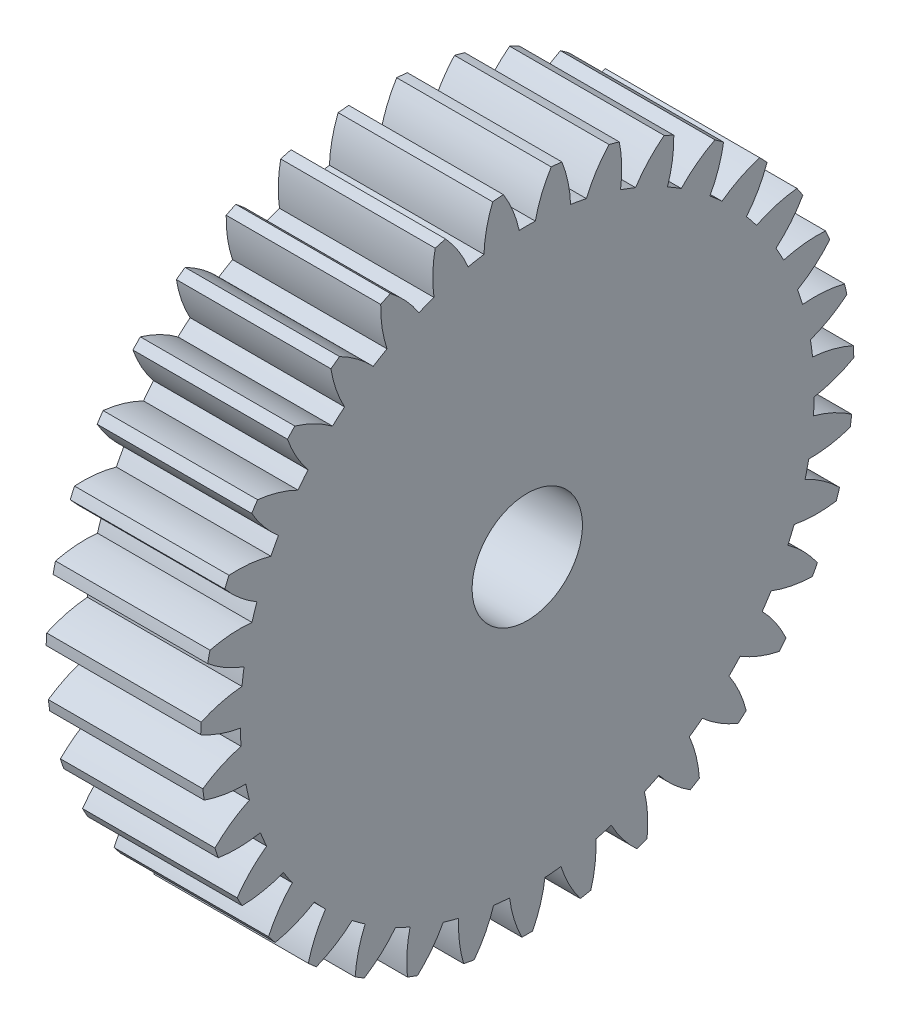
SolidWorks part; units mm, degrees
ref_plane "Plane1" through (0, 0, 0) normal (0, 0, 1) x (1, 0, 0)
ref_plane "Plane2" through (0, 0, 0) normal (0, 1, 0) x (1, 0, 0)
ref_plane "Plane3" through (0, 0, 0) normal (1, 0, 0) x (0, 0, -1)
sketch "HoldingSke" plane through (0, 0, 0) normal (0, 1, 0) x (1, 0, 0)
  line L0 (0, 0) -> (1.0239, -0.717)
  line L1 (-15, 0) -> (100, 0) construction
  line L2 (0, 0) -> (-2.1039, 2.3779)
  line L3 (0, 0) -> (-11.863, 4.5341)
  line L4 (0, 0) -> (7.0742, 4.9534)
  line L5 (0, 0) -> (-46.8476, -17.4728)
  line L6 (0, 0) -> (-5.8027, -3.9151)
  line L7 (-2.1039, 2.3779) -> (8.6586, 51.2059)
  line L8 (-76.2, 54.61) -> (-75.3, 54.61)
  line L9 (-71.009, 38.7566) -> (-53.1078, 45.2721)
  line L10 (-76.2, 71.12) -> (104.1128, 71.12)
  line L11 (0, 0) -> (-7, 0)
  line L12 (-76.2, 101.6) -> (-76.17, 101.6)
  line L13 (24.9733, 27.94) -> (52.9518, 28.4284)
  line L14 (24.9733, 27.94) -> (24.9743, 27.94)
  line L15 (24.9733, 27.94) -> (100.4006, 29.5858)
  line L16 (-63.627, -0.8) -> (-12.827, -0.8)
  circle A0 centre (0, 0) radius 2.5
  circle A1 centre (0, 0) radius 12.999
  circle A2 centre (0, 0) radius 37.5
  circle A3 centre (0, 0) radius 2.5
  dimension "MHD" = 25.998
  dimension "Hub_dia" = 75
  dimension "Bore" = 5
  dimension "MBD" = 5
  dimension "Num_teeth" = 35
  dimension "Pitch" = 1.25
  dimension "Overall_len" = 50
  dimension "Show_teeth" = 35
  dimension "Thickness" = 7
  dimension "OAL" = 50.0001
  dimension "T_dim" = 0.9
  dimension "Ap" = 20
  dimension "H" = 19.05
  dimension "Pitch_radius" = 180.3128
  dimension "Width" = 7
  dimension "Backlash" = 0.03
  dimension "Addendum_fac" = 1
  dimension "Dedendum_fac" = 1.25
  dimension "Clearance_fac" = 0.25
  dimension "Dedendum_add" = 0.001
  dimension "Module" = 0.8
sketch "BasProSke" plane through (0, 0, 0) normal (0, 1, 0) x (1, 0, 0)
  line L0 (-10, 0) -> (60, 0) construction
  line L1 (0, 0) -> (0, 14.8)
  line L2 (0, 0) -> (7, 0)
  line L3 (7, 0) -> (7, 14.8)
  line L4 (7, 14.8) -> (0, 14.8)
  dimension "Thickness" = 7
  dimension "Diameter" = 29.6
revolve "Base-Revolve" add sketch "BasProSke" angle 360 about L0
sketch "TooCutSke" plane through (0, 0, 0) normal (1, 0, 0) x (0, 0, -1)
  line L1 (0, 0) -> (0, 107) construction
  line L2 (0, 0) -> (-0.6806, 13.9834) construction
  line L3 (0, 0) -> (-2.5078, 27.8637) construction
  line L4 (-0.6806, 13.9834) -> (-1.2539, 13.9318) construction
  arc A0 (0.3644, 12.9939) -> (-0.3644, 12.9939) centre (0, 0) ccw
  arc A1 (1.1007, 14.7845) -> (-1.1007, 14.7845) centre (0, 0) ccw
  circle A2 centre (0, 0) radius 14 construction
  circle A3 centre (0, 0) radius 13.1557 construction
  arc A4 (-0.3644, 12.9939) -> (-1.1007, 14.7845) centre (-5.8338, 11.7915) ccw
  arc A5 (1.1007, 14.7845) -> (0.3644, 12.9939) centre (5.8338, 11.7915) ccw
  dimension "Root_dia" = 25.998
  dimension "Overcut_dia" = 29.6508
  dimension "Pitch_dia" = 28
  dimension "Base_dia" = 26.3114
  dimension "Flank_rad" = 5.6
  dimension "Half_ang" = 5.143
  dimension "Half_CT" = 0.5756
extrude "ToothCut" cut sketch "TooCutSke" along normal through all
fillet "Breaks" [suppressed] radius 0.016
fillet "RootFillets" [suppressed] radius 0.201
pattern_circular "TeethCuts" count 35 every 10.286 about axis through (-10, 0, 0) along (1, 0, 0) of "ToothCut", "RootFillets", "Breaks"
sketch "HubNeaOneSke" plane through (0, 0, 0) normal (-1, 0, 0) x (0, 0, 1)
  circle A0 centre (0, 0) radius 12.999
  dimension "Diameter" = 25.998
extrude "HubNearOne" [suppressed] add sketch "HubNeaOneSke" along normal blind 43.0001
sketch "HubNeaBotSke" plane through (0, 0, 0) normal (-1, 0, 0) x (0, 0, 1)
  circle A0 centre (0, 0) radius 12.999
  dimension "Diameter" = 25.998
extrude "HubNearBoth" [suppressed] add sketch "HubNeaBotSke" along normal blind 21.5
ref_plane "FarPln" through (7, 0, 0) normal (1, 0, 0) x (0, 0, -1)
sketch "HubFarSke" plane through (7, 0, 0) normal (1, 0, 0) x (0, 0, -1)
  circle A0 centre (0, 0) radius 12.999
  dimension "Diameter" = 25.998
extrude "HubFar" [suppressed] add sketch "HubFarSke" along normal blind 21.5
sketch "BorSke" plane through (0, 0, 0) normal (1, 0, 0) x (0, 0, -1)
  circle A0 centre (0, 0) radius 2.5
  dimension "Diameter" = 5
extrude "Bore" cut sketch "BorSke" along normal mid plane 100.0001
sketch "KeySke" plane through (0, 0, 0) normal (1, 0, 0) x (0, 0, -1)
  line L0 (-1, 0) -> (-1, 3.4)
  line L1 (-1, 3.4) -> (1, 3.4)
  line L2 (1, 3.4) -> (1, 0)
  line L3 (0, 0) -> (0, 34) construction
  line L4 (-1, 0) -> (1, 0)
  dimension "Offset" = 3.4
  dimension "Width" = 2
extrude "Keyway" [suppressed] cut sketch "KeySke" along normal mid plane 100.0001
pattern_circular "Keyway2" [suppressed] count 2 every 90 about axis through (-10, 0, 0) along (1, 0, 0)
equation "' \"Module@HoldingSke\" = 6.35"
equation "' \"Num_teeth@HoldingSke\" = 12"
equation "' \"Ap@HoldingSke\" =  20"
equation "' \"Ap@HoldingSke\" = 20"
equation "' \"Width@HoldingSke\" = 0.5 * 25.4"
equation "' \"Hub_dia@HoldingSke\"= 1 * 25.4"
equation "' \"Hub_dia@HoldingSke\" = 1 * 25.4"
equation "' \"Overall_len@HoldingSke\" = 1.0 * 25.4"
equation "' \"Bore@HoldingSke\" = 0.75 * 25.4"
equation "' \"T_dim@HoldingSke\" = 0.1 * 25.4"
equation "' \"Width@KeySke\" = 0.25 * 25.4"
equation "' \"Show_teeth@HoldingSke\" = 13"
equation "' \"Backlash@HoldingSke\" = 0.009 * 25.4"
equation "' \"Addendum_fac@HoldingSke\" = 1.0"
equation "' \"Dedendum_fac@HoldingSke\" = 1.25"
equation "' \"Dedendum_add@HoldingSke\" = 0.00005 * 25.4"
equation "' \"Clearance_fac@HoldingSke\" = 0.25"
equation "\"Pitch@HoldingSke\" = 1 / \"Module@HoldingSke\""
equation "\"Overcut_dia@TooCutSke\" = (\"Num_teeth@HoldingSke\" + 2 * \"Addendum_fac@HoldingSke\") / \"Pitch@HoldingSke\" + 0.002 * 25.4"
equation "\"Pitch_dia@TooCutSke\" = \"Num_teeth@HoldingSke\" / \"Pitch@HoldingSke\""
equation "\"Base_dia@TooCutSke\" = \"Num_teeth@HoldingSke\" / \"Pitch@HoldingSke\" * cos((\"Ap@HoldingSke\"  * 3.14159265 / 180))"
equation "\"Root_dia@TooCutSke\" = (\"Num_teeth@HoldingSke\" + 2) / \"Pitch@HoldingSke\" - 2 * (\"Addendum_fac@HoldingSke\" + \"Dedendum_fac@HoldingSke\") / \"Pitch@HoldingSke\" - \"Dedendum_add@HoldingSke\" * 2"
equation "\"Half_ang@TooCutSke\" = 180 / \"Num_teeth@HoldingSke\""
equation "\"Half_CT@TooCutSke\" = \"Num_teeth@HoldingSke\" / \"Pitch@HoldingSke\" * sin((3.14159265 / 2 / \"Num_teeth@HoldingSke\")) / 2 - 7 * \"Backlash@HoldingSke\" / 4"
equation "\"Flank_rad@TooCutSke\" = \"Num_teeth@HoldingSke\" / \"Pitch@HoldingSke\" / 5"
equation "\"Radius@RootFillets\" = \"Clearance_fac@HoldingSke\" / \"Pitch@HoldingSke\" + \"Dedendum_add@HoldingSke\""
equation "\"Break_rad@Breaks\" = 0.02 / \"Pitch@HoldingSke\""
equation "\"Thickness@HoldingSke\" = \"Width@HoldingSke\""
equation "\"OAL@HoldingSke\" = \"Thickness@HoldingSke\""
equation "\"MHD@HoldingSke\" = (\"Num_teeth@HoldingSke\" + 2) / \"Pitch@HoldingSke\" - 2 * (\"Addendum_fac@HoldingSke\" + \"Dedendum_fac@HoldingSke\")  / \"Pitch@HoldingSke\" - \"Dedendum_add@HoldingSke\" * 2"
equation "\"MBD@HoldingSke\" = (\"Num_teeth@HoldingSke\" + 2) / \"Pitch@HoldingSke\" - 2 * (\"Addendum_fac@HoldingSke\" + \"Dedendum_fac@HoldingSke\")  / \"Pitch@HoldingSke\" - \"Dedendum_add@HoldingSke\" * 2 - 0.002 * 25.4"
equation "\"MHD@HoldingSke\" = ((sgn( \"MHD@HoldingSke\" - \"Hub_dia@HoldingSke\" )-1)*( \"MHD@HoldingSke\" - \"Hub_dia@HoldingSke\" ))/-2+ \"Hub_dia@HoldingSke\""
equation "\"MBD@HoldingSke\" = ((sgn( \"MBD@HoldingSke\" - \"Bore@HoldingSke\" )-1)*( \"MBD@HoldingSke\" - \"Bore@HoldingSke\" ))/-2+ \"Bore@HoldingSke\""
equation "\"OAL@HoldingSke\" = ((sgn( \"OAL@HoldingSke\" - \"Overall_len@HoldingSke\" )+1)*( \"OAL@HoldingSke\" - \"Overall_len@HoldingSke\" ))/2 + \"Overall_len@HoldingSke\" + 0.000002 * 25.4"
equation "\"Num_teeth@TeethCuts\" = int( \"Show_teeth@HoldingSke\" ) + 1"
equation "\"Num_teeth@TeethCuts\" = ((sgn( \"Num_teeth@TeethCuts\" - \"Num_teeth@HoldingSke\" )-1)*( \"Num_teeth@TeethCuts\" - \"Num_teeth@HoldingSke\" ))/-2+ \"Num_teeth@HoldingSke\""
equation "\"Num_teeth@TeethCuts\" = ((sgn( \"Num_teeth@TeethCuts\" - 2.0)+1)*( \"Num_teeth@TeethCuts\" - 2.0))/2 +2.0"
equation "\"Angle@TeethCuts\" = 360.0 / \"Num_teeth@HoldingSke\""
equation "\"Diameter@BasProSke\" = (\"Num_teeth@HoldingSke\" + 2 * \"Addendum_fac@HoldingSke\") / \"Pitch@HoldingSke\""
equation "\"Thickness@BasProSke\"  = \"Thickness@HoldingSke\""
equation "' \"Fillet_rad@BasProSke\" =  \"Thickness@HoldingSke\" * 0.05"
equation "' \"Fillet_rad@BasProSke\" = \"Thickness@HoldingSke\" * 0.05"
equation "\"MHD@HoldingSke\" = ((sgn( \"MHD@HoldingSke\" - \"Root_dia@TooCutSke\" )-1)*( \"MHD@HoldingSke\" - \"Root_dia@TooCutSke\" ))/-2+ \"Root_dia@TooCutSke\""
equation "\"Diameter@HubNeaOneSke\" = \"MHD@HoldingSke\""
equation "\"Length@HubNearOne\" = \"OAL@HoldingSke\" - \"Thickness@BasProSke\""
equation "\"Diameter@HubNeaBotSke\" = \"MHD@HoldingSke\""
equation "\"Length@HubNearBoth\" = ( \"OAL@HoldingSke\" - \"Thickness@BasProSke\" ) / 2.0"
equation "\"Thickness@FarPln\" = \"Thickness@BasProSke\""
equation "\"Diameter@HubFarSke\" = \"MHD@HoldingSke\""
equation "\"Length@HubFar\" = ( \"OAL@HoldingSke\" - \"Thickness@BasProSke\" ) / 2.0"
equation "\"Diameter@BorSke\" = \"MBD@HoldingSke\""
equation "\"D1@Bore\" = \"OAL@HoldingSke\" * 2.0"
equation "\"D1@Keyway\" = \"OAL@HoldingSke\" * 2.0"
equation "\"Offset@KeySke\" = \"T_dim@HoldingSke\" + \"MBD@HoldingSke\" / 2.0"
